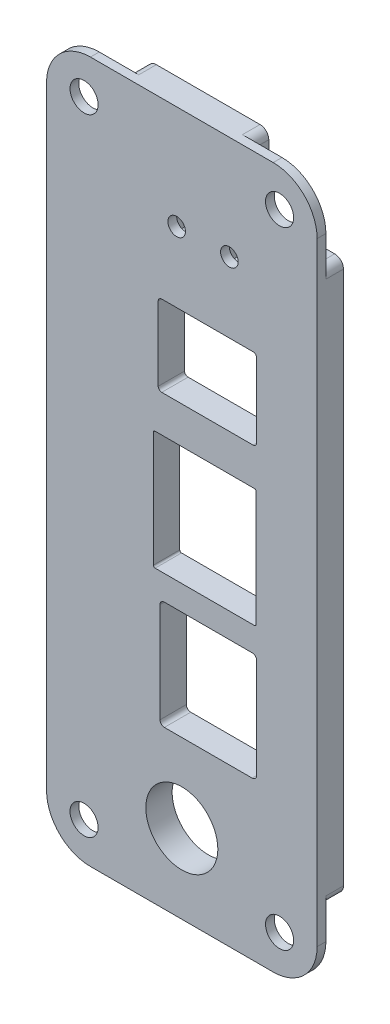
SolidWorks part; units mm, degrees
ref_plane "Front Plane" through (0, 0, 0) normal (0, 0, 1) x (1, 0, 0)
ref_plane "Top Plane" through (0, 0, 0) normal (0, 1, 0) x (1, 0, 0)
ref_plane "Right Plane" through (0, 0, 0) normal (1, 0, 0) x (0, 0, -1)
other "Configuration Table"
sketch "草图1" plane through (0, 0, 0) normal (0, 0, 1) x (1, 0, 0)
  line L0 (47.5, 0) -> (47.4, 0) construction
  line L1 (47.5, -35) -> (47.5, 35) construction
  line L2 (47.4, -34.9) -> (47.4, 34.9)
  line L3 (32, 40) -> (32, 39.9) construction
  line L4 (42.5, 40) -> (21.5, 40) construction
  line L5 (21.6, 39.9) -> (42.4, 39.9)
  line L8 (21.6, -39.9) -> (42.4, -39.9)
  line L9 (21.6, -39.9) -> (42.4, -39.9)
  line L10 (21.6, 39.9) -> (42.4, 39.9)
  line L15 (16.5, 0) -> (16.6, 0) construction
  line L16 (40.4138, -15.8026) -> (40.5139, -15.8026) construction
  line L17 (40.5139, -21.4776) -> (40.5139, -10.1276)
  line L18 (16.6, -34.9) -> (16.6, 34.9)
  line L19 (30.0139, -21.9776) -> (40.0139, -21.9776)
  line L20 (37.4138, 28.1024) -> (31.4138, 28.1024) construction
  line L22 (30.0139, -9.6276) -> (40.0139, -9.6276)
  line L25 (29.5139, -21.4776) -> (29.5139, -10.1276)
  line L31 (40.3644, -0.0546) -> (40.465, -0.0546) construction
  line L34 (40.465, 6.4954) -> (40.465, -6.6046)
  line L35 (34.6144, 6.5954) -> (34.6144, 6.6954) construction
  line L36 (28.9639, 6.6954) -> (40.265, 6.6954)
  line L38 (28.8639, -0.0546) -> (28.7639, -0.0546) construction
  line L39 (28.7639, 6.4954) -> (28.7639, -6.6046)
  line L40 (34.6139, -6.7046) -> (34.6139, -6.8046) construction
  line L41 (28.9639, -6.8046) -> (40.265, -6.8046)
  line L50 (40.5138, 11.3024) -> (40.5138, 19.7024)
  line L51 (29.7138, 20.1024) -> (40.1138, 20.1024)
  line L52 (29.3138, 11.3024) -> (29.3138, 19.7024)
  line L53 (29.7138, 10.9024) -> (40.1138, 10.9024)
  arc A0 (42.4, -39.9) -> (47.4, -34.9) centre (42.4, -34.9) ccw
  arc A1 (21.6, -39.9) -> (16.6, -34.9) centre (21.6, -34.9) cw
  arc A2 (47.4, 34.9) -> (42.4, 39.9) centre (42.4, 34.9) ccw
  arc A3 (16.6, 34.9) -> (21.6, 39.9) centre (21.6, 34.9) cw
  arc A4 (30.0139, -21.9776) -> (29.5139, -21.4776) centre (30.0139, -21.4776) cw
  arc A5 (40.0139, -21.9776) -> (40.5139, -21.4776) centre (40.0139, -21.4776) ccw
  arc A6 (40.5139, -10.1276) -> (40.0139, -9.6276) centre (40.0139, -10.1276) ccw
  arc A7 (29.5139, -10.1276) -> (30.0139, -9.6276) centre (30.0139, -10.1276) cw
  arc A8 (28.7639, 6.4954) -> (28.9639, 6.6954) centre (28.9639, 6.4954) cw
  arc A9 (40.465, 6.4954) -> (40.265, 6.6954) centre (40.265, 6.4954) ccw
  arc A10 (28.9639, -6.8046) -> (28.7639, -6.6046) centre (28.9639, -6.6046) cw
  arc A11 (40.265, -6.8046) -> (40.465, -6.6046) centre (40.265, -6.6046) ccw
  arc A12 (29.7138, 10.9024) -> (29.3138, 11.3024) centre (29.7138, 11.3024) cw
  arc A13 (40.1138, 10.9024) -> (40.5138, 11.3024) centre (40.1138, 11.3024) ccw
  arc A14 (40.5138, 19.7024) -> (40.1138, 20.1024) centre (40.1138, 19.7024) ccw
  arc A15 (29.3138, 19.7024) -> (29.7138, 20.1024) centre (29.7138, 19.7024) cw
  circle A16 centre (37.4138, 28.1024) radius 1
  circle A17 centre (31.4138, 28.1024) radius 1
  point P6 (0, 0)
  point P10 (0, 0)
  point P16 (32, -39.9)
  point P36 (40.5139, -15.8026)
  point P39 (35.0139, -21.9776)
  point P46 (35.0139, -9.6276)
  point P53 (29.5139, -15.8026)
  point P58 (40.4644, -0.0546)
  point P72 (40.465, -0.0546)
  point P78 (34.6144, 6.6954)
  point P84 (28.7639, -0.0546)
  point P89 (34.6139, -6.8046)
  point P112 (40.5138, 15.5024)
  point P117 (34.9138, 20.1024)
  point P118 (29.3138, 15.5024)
  point P123 (34.9138, 10.9024)
  dimension "D1" = 5
  dimension "D2" = 0.5
  dimension "D3" = 0.2
  dimension "D4" = 0.4
  dimension "D5" = 8
extrude "凸台-拉伸1" add sketch "草图1" against normal blind 3
sketch "草图2" plane through (0, 0, -3) normal (0, 0, -1) x (-1, 0, 0)
  line L0 (-16.6, -19) -> (-16.6, 19)
  line L2 (-16.6, -34.9) -> (-16.6, 34.9) construction
  line L3 (-16.6, -19) -> (-27.6, -19)
  line L4 (-27.6, -19) -> (-27.6, 19)
  line L5 (-27.6, 19) -> (-16.6, 19)
  point P5 (-16.6, 0)
extrude "切除-拉伸1" cut sketch "草图2" against normal blind 1
sketch "草图3" plane through (0, 0, -3) normal (0, 0, -1) x (-1, 0, 0)
  line L0 (-47.4, -31.4) -> (-38.9, -31.4)
  line L1 (-47.4, -34.9) -> (-47.4, 34.9) construction
  line L2 (-38.9, -31.4) -> (-38.9, -39.9)
  line L3 (-21.6, -39.9) -> (-42.4, -39.9) construction
  line L5 (-42.4, -39.9) -> (-38.9, -39.9)
  line L6 (-47.4, -34.9) -> (-47.4, -31.4)
  line L7 (-47.4, 0) -> (-16.6, 0) construction
  line L8 (-16.6, -19) -> (-16.6, 19) construction
  line L9 (-32, 0) -> (-32, -4.0641) construction
  line L10 (-47.4, 34.9) -> (-47.4, 31.4)
  line L11 (-42.4, 39.9) -> (-38.9, 39.9)
  line L12 (-38.9, 31.4) -> (-38.9, 39.9)
  line L13 (-47.4, 31.4) -> (-38.9, 31.4)
  line L15 (-16.6, 31.4) -> (-25.1, 31.4)
  line L16 (-25.1, 31.4) -> (-25.1, 39.9)
  line L17 (-21.6, 39.9) -> (-25.1, 39.9)
  line L18 (-16.6, 34.9) -> (-16.6, 31.4)
  line L19 (-16.6, -34.9) -> (-16.6, -31.4)
  line L20 (-21.6, -39.9) -> (-25.1, -39.9)
  line L21 (-25.1, -31.4) -> (-25.1, -39.9)
  line L22 (-16.6, -31.4) -> (-25.1, -31.4)
  arc A0 (-42.4, -39.9) -> (-47.4, -34.9) centre (-42.4, -34.9) cw
  arc A1 (-42.4, 39.9) -> (-47.4, 34.9) centre (-42.4, 34.9) ccw
  arc A2 (-21.6, 39.9) -> (-16.6, 34.9) centre (-21.6, 34.9) cw
  arc A3 (-21.6, -39.9) -> (-16.6, -34.9) centre (-21.6, -34.9) ccw
extrude "切除-拉伸2" cut sketch "草图3" against normal blind 2
sketch "草图4" plane through (0, 0, -1) normal (0, 0, -1) x (-1, 0, 0)
  line L0 (-47.4, 0) -> (-16.6, 0) construction
  line L1 (-47.4, -31.4) -> (-47.4, 31.4) construction
  line L2 (-16.6, -19) -> (-16.6, 19) construction
  line L3 (-32, 0) -> (-32, -3.4003) construction
  circle A0 centre (-20.8723, 35.6277) radius 1.6
  circle A2 centre (-20.8723, -35.6277) radius 1.6
  circle A3 centre (-43.1277, -35.6277) radius 1.6
  circle A4 centre (-43.1277, 35.6277) radius 1.6
extrude "切除-拉伸3" cut sketch "草图4" against normal through all
sketch "草图6" plane through (0, 0, -3) normal (0, 0, -1) x (-1, 0, 0)
  line L1 (-38.7138, 29.8524) -> (-36.1138, 29.8524)
  line L2 (-38.7138, 29.8524) -> (-38.7138, 26.3524)
  line L3 (-38.7138, 26.3524) -> (-36.1138, 26.3524)
  line L4 (-36.1138, 29.8524) -> (-36.1138, 26.3524)
  line L5 (-38.7138, 29.8524) -> (-36.1138, 26.3524) construction
  line L6 (-38.7138, 26.3524) -> (-36.1138, 29.8524) construction
  line L7 (-32.6638, 29.8524) -> (-30.1638, 29.8524)
  line L8 (-32.6638, 29.8524) -> (-32.6638, 26.3524)
  line L9 (-32.6638, 26.3524) -> (-30.1638, 26.3524)
  line L10 (-30.1638, 29.8524) -> (-30.1638, 26.3524)
  line L11 (-32.6638, 29.8524) -> (-30.1638, 26.3524) construction
  line L12 (-32.6638, 26.3524) -> (-30.1638, 29.8524) construction
  point P0 (-37.4138, 28.1024)
  point P7 (-31.4138, 28.1024)
extrude "切除-拉伸4" cut sketch "草图6" against normal blind 2
sketch "草图7" plane through (0, 0, 0) normal (0, 0, 1) x (1, 0, 0)
  line L0 (32, -39.9) -> (32, -21.9776) construction
  line L1 (30.0139, -21.9776) -> (40.0139, -21.9776) construction
  circle A1 centre (32, -30.9388) radius 4.1
extrude "切除-拉伸5" cut sketch "草图7" against normal through all
fillet "圆角1" radius 1 8 edges at (47.4, 31.4, -2) (47.4, -31.4, -2) (38.9, -39.9, -2) (25.1, -39.9, -2) (16.6, -31.4, -2) (38.9, 39.9, -2) (25.1, 39.9, -2) (16.6, 31.4, -2)
